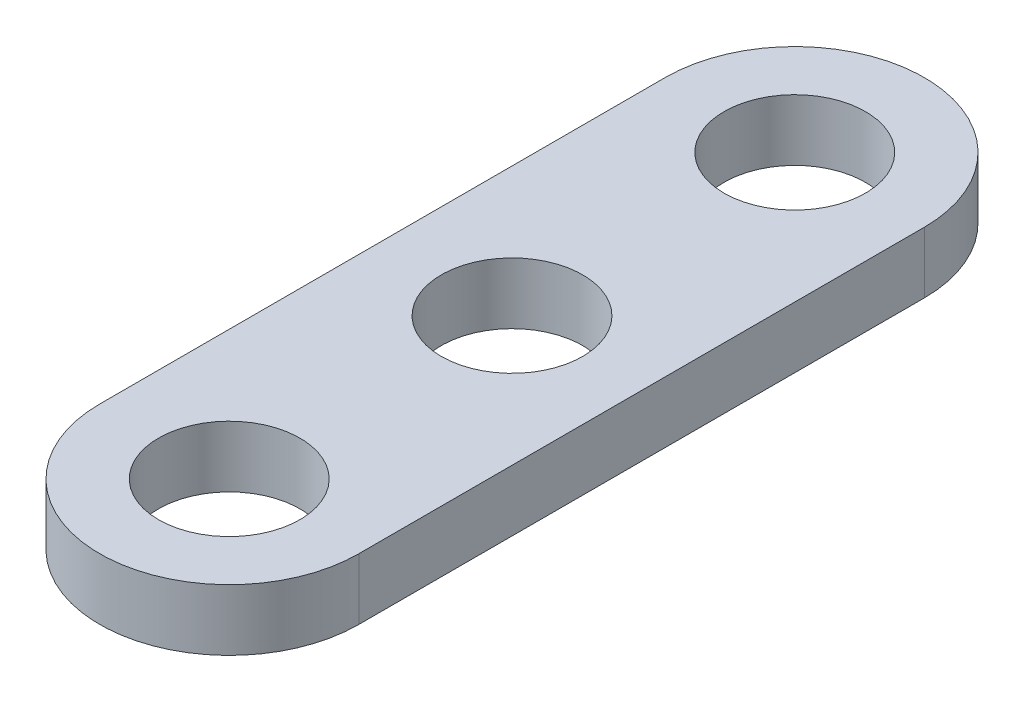
SolidWorks part; units mm, degrees
ref_plane "Front Plane" through (0, 0, 0) normal (0, 0, 1) x (1, 0, 0)
ref_plane "Top Plane" through (0, 0, 0) normal (0, 1, 0) x (1, 0, 0)
ref_plane "Right Plane" through (0, 0, 0) normal (1, 0, 0) x (0, 0, -1)
sketch "Sketch1" plane through (0, 0, 0) normal (0, 1, 0) x (1, 0, 0)
  line L0 (0, 6.0877) -> (0, -17.9123) construction
  line L1 (5.5, 6.0877) -> (5.5, -17.9123)
  line L2 (-5.5, 6.0877) -> (-5.5, -17.9123)
  arc A0 (5.5, 6.0877) -> (-5.5, 6.0877) centre (0, 6.0877) ccw
  arc A1 (-5.5, -17.9123) -> (5.5, -17.9123) centre (0, -17.9123) ccw
  circle A2 centre (0, 6.0877) radius 3
  circle A3 centre (0, -17.9123) radius 3
  circle A4 centre (0, -5.9123) radius 3
  point P3 (0, -5.9123)
  dimension "D1" = 5.5
  dimension "D3" = 6
  dimension "D4" = 6
  dimension "D5" = 6
  dimension "D2" = 24
extrude "Boss-Extrude1" add sketch "Sketch1" along normal blind 2.6
